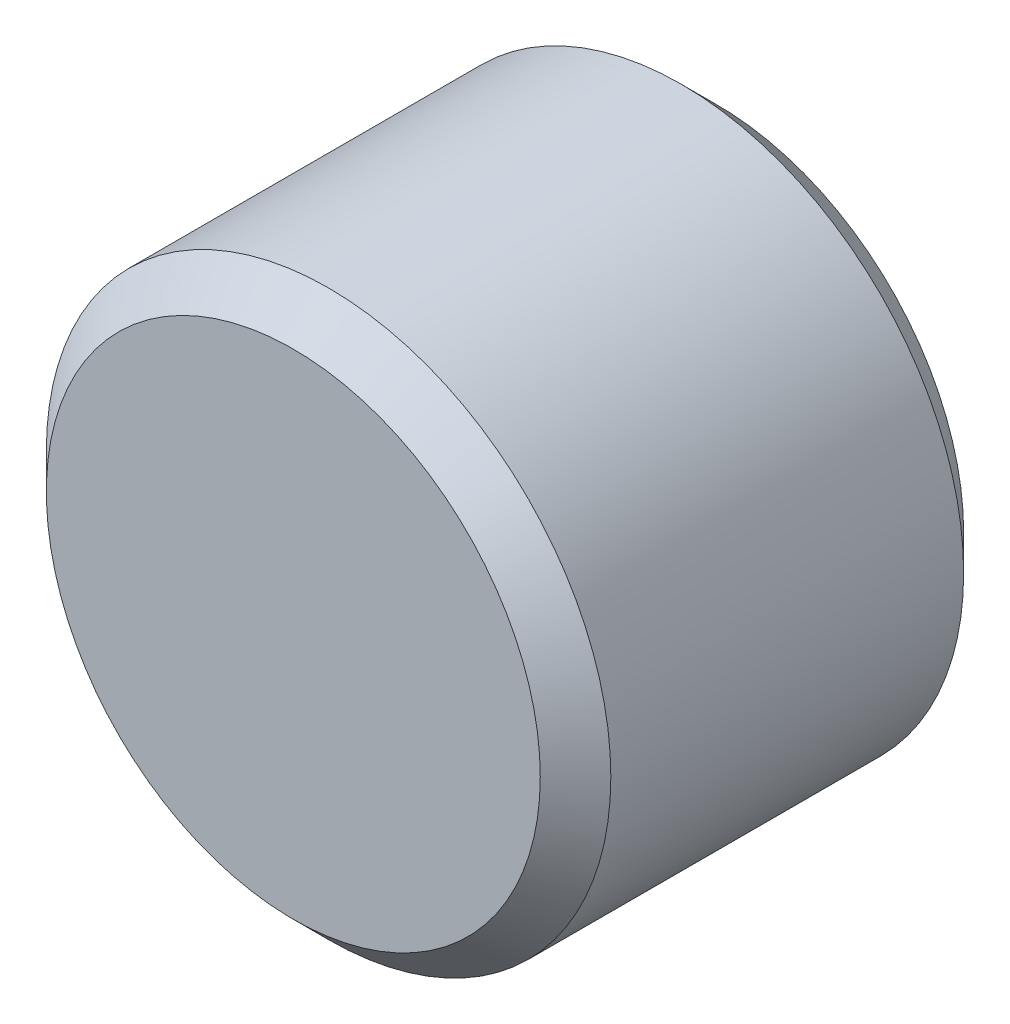
SolidWorks part; units mm, degrees
ref_plane "Front Plane" through (0, 0, 0) normal (0, 0, 1) x (1, 0, 0)
ref_plane "Top Plane" through (0, 0, 0) normal (0, 1, 0) x (1, 0, 0)
ref_plane "Right Plane" through (0, 0, 0) normal (1, 0, 0) x (0, 0, -1)
sketch "Sketch1" plane through (0, 0, 0) normal (0, 0, 1) x (1, 0, 0)
  circle A0 centre (0, 0) radius 4
  dimension "D1" = 8
extrude "Boss-Extrude1" add sketch "Sketch1" along normal blind 6
chamfer "Chamfer1" distance 0.5 angle 45 2 edges at (4, 0, 0) (4, 0, 6)
